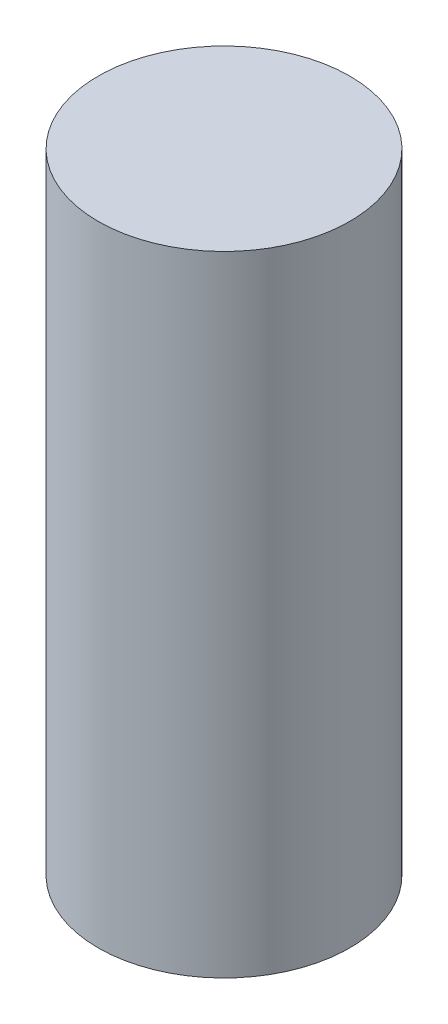
SolidWorks part; units mm, degrees
ref_plane "Front Plane" through (0, 0, 0) normal (0, 0, 1) x (1, 0, 0)
ref_plane "Top Plane" through (0, 0, 0) normal (0, 1, 0) x (1, 0, 0)
ref_plane "Right Plane" through (0, 0, 0) normal (1, 0, 0) x (0, 0, -1)
sketch "Reconstructed nominal axial profile" plane through (0, 0, 0) normal (0, 0, 1) x (1, 0, 0)
  line L0 (0, -500) -> (0, 50) construction
  line L1 (0, 0) -> (0, 20)
  line L2 (0, 20) -> (4, 20)
  line L3 (4, 20) -> (4, 0)
  line L4 (4, 0) -> (0, 0)
revolve "Native revolved geometry" add sketch "Reconstructed nominal axial profile" angle 360 about L0
